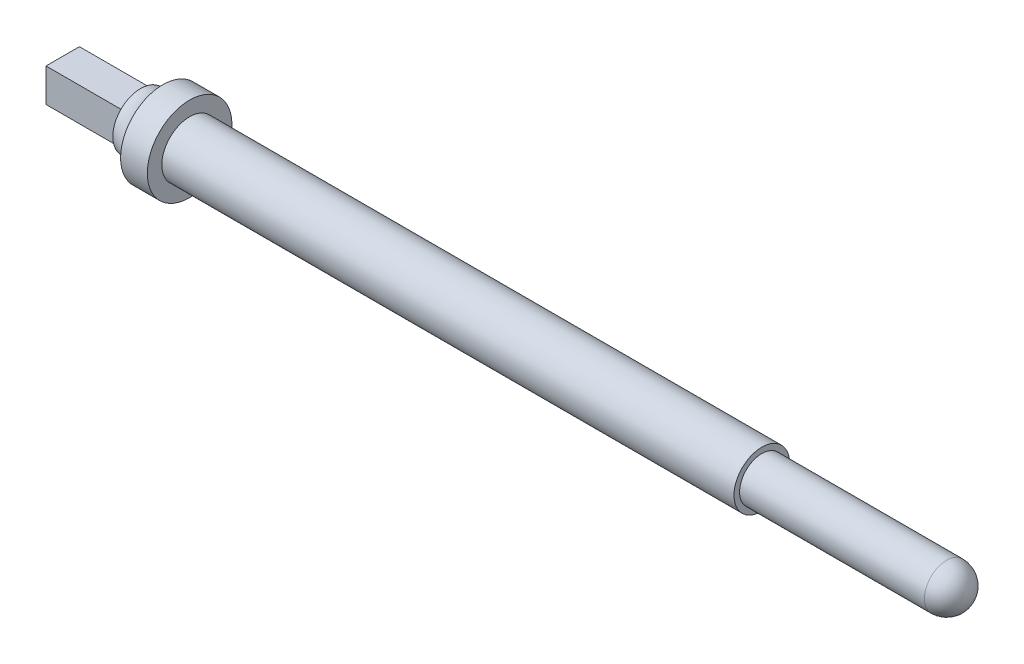
SolidWorks part; units mm, degrees
ref_plane "Front Plane" through (0, 0, 0) normal (0, 0, 1) x (1, 0, 0)
ref_plane "Top Plane" through (0, 0, 0) normal (0, 1, 0) x (1, 0, 0)
ref_plane "Right Plane" through (0, 0, 0) normal (1, 0, 0) x (0, 0, -1)
sketch "Sketch1" plane through (0, 0, 0) normal (0, 0, 1) x (1, 0, 0)
  line L0 (-14.3328, 0) -> (369.0073, 0) construction
  line L1 (0, 0) -> (0, 19)
  line L2 (0, 19) -> (12, 19)
  line L3 (12, 19) -> (12, 12.5)
  line L4 (12, 12.5) -> (269, 12.5)
  line L5 (-10, 0) -> (362, 0)
  line L6 (269, 12.5) -> (269, 10)
  line L7 (269, 10) -> (352, 10)
  line L9 (-10, 12.5) -> (-10, 0)
  arc A0 (362, 0) -> (352, 10) centre (352, 0) ccw
  arc A1 (-10, 12.5) -> (0, 19) centre (-10.7389, 24.5791) ccw
  point P13 (-10, 12.5)
  dimension "D8" = 362
  dimension "D1" = 19
  dimension "D2" = 12
  dimension "D4" = 257
  dimension "D7" = 10
revolve "Revolve1" add sketch "Sketch1" angle 360 about L0
sketch "Sketch2" plane through (-10, 0, 0) normal (-1, 0, 0) x (0, 0, 1)
  line L1 (7.5, -7.5) -> (-7.5, -7.5)
  line L2 (7.5, -7.5) -> (7.5, 7.5)
  line L3 (7.5, 7.5) -> (-7.5, 7.5)
  line L4 (-7.5, -7.5) -> (-7.5, 7.5)
  line L5 (7.5, -7.5) -> (-7.5, 7.5) construction
  line L6 (7.5, 7.5) -> (-7.5, -7.5) construction
  point P0 (0, 0)
  dimension "D1" = 15
  dimension "D2" = 15
extrude "Boss-Extrude1" add sketch "Sketch2" along normal blind 35
